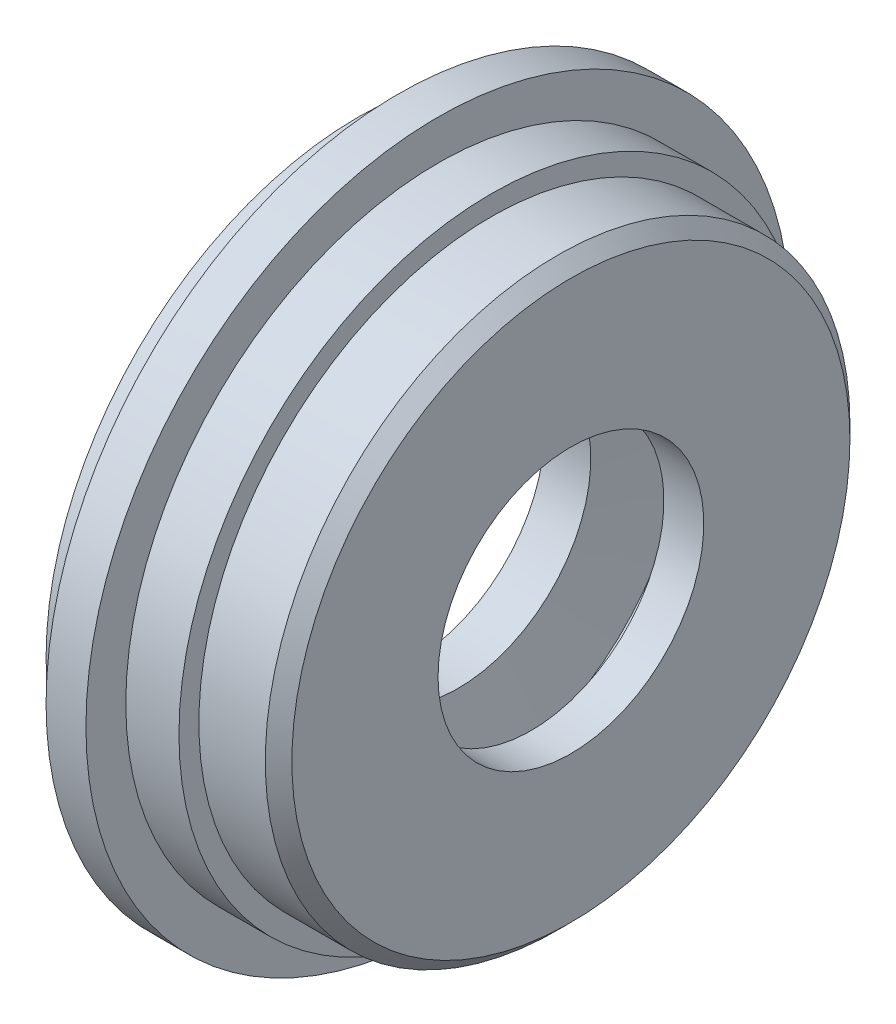
SolidWorks part; units mm, degrees
ref_plane "前视基准面" through (0, 0, 0) normal (0, 0, 1) x (1, 0, 0)
ref_plane "上视基准面" through (0, 0, 0) normal (0, 1, 0) x (1, 0, 0)
ref_plane "右视基准面" through (0, 0, 0) normal (1, 0, 0) x (0, 0, -1)
sketch "草图1" plane through (0, 0, 0) normal (1, 0, 0) x (0, 0, -1)
  circle A0 centre (0, 0) radius 23.5
  dimension "D1" = 47
extrude "凸台-拉伸1" add sketch "草图1" along normal blind 10
sketch "草图2" plane through (10, 0, 0) normal (1, 0, 0) x (0, 0, -1)
  circle A0 centre (0, 0) radius 22
  dimension "D1" = 44
extrude "凸台-拉伸2" add sketch "草图2" along normal blind 6
sketch "草图3" plane through (0, 0, 0) normal (-1, 0, 0) x (0, 0, 1)
  circle A0 centre (0, 0) radius 26.5
  dimension "D1" = 53
extrude "凸台-拉伸3" add sketch "草图3" against normal blind 3 from offset 3 offset against normal yes
sketch "草图4" plane through (0, 0, 0) normal (-1, 0, 0) x (0, 0, 1)
  circle A0 centre (0, 0) radius 18.5
  dimension "D1" = 37
extrude "切除-拉伸1" cut sketch "草图4" against normal blind 4
sketch "草图5" plane through (4, 0, 0) normal (-1, 0, 0) x (0, 0, 1)
  circle A0 centre (0, 0) radius 10
  dimension "D1" = 20
extrude "切除-拉伸2" cut sketch "草图5" against normal through all
sketch "草图7" plane through (0, 0, 0) normal (0, 1, 0) x (1, 0, 0)
  line L0 (0, 0) -> (19.2153, 0) construction
  line L1 (0, 18.5) -> (0, -18.5) construction
  line L2 (13, 0) -> (7.5, 0)
  line L3 (7.5, 0) -> (7.5, -10)
  line L4 (7.5, -10) -> (8.25, -16.5)
  line L5 (8.25, -16.5) -> (12.25, -16.5)
  line L6 (10.25, -16.5) -> (10.25, -10.9924) construction
  line L7 (13, 0) -> (13, -10)
  line L8 (13, -10) -> (12.25, -16.5)
  line L9 (16, -10) -> (16, 10) construction
  dimension "D1" = 5.5
  dimension "D2" = 10
  dimension "D3" = 4
  dimension "D4" = 16.5
  dimension "D5" = 3
revolve "切除-旋转1" cut sketch "草图7" angle 360 about L0
chamfer "倒角1" distance 1 angle 45 1 edges at (16, 0, -22)
